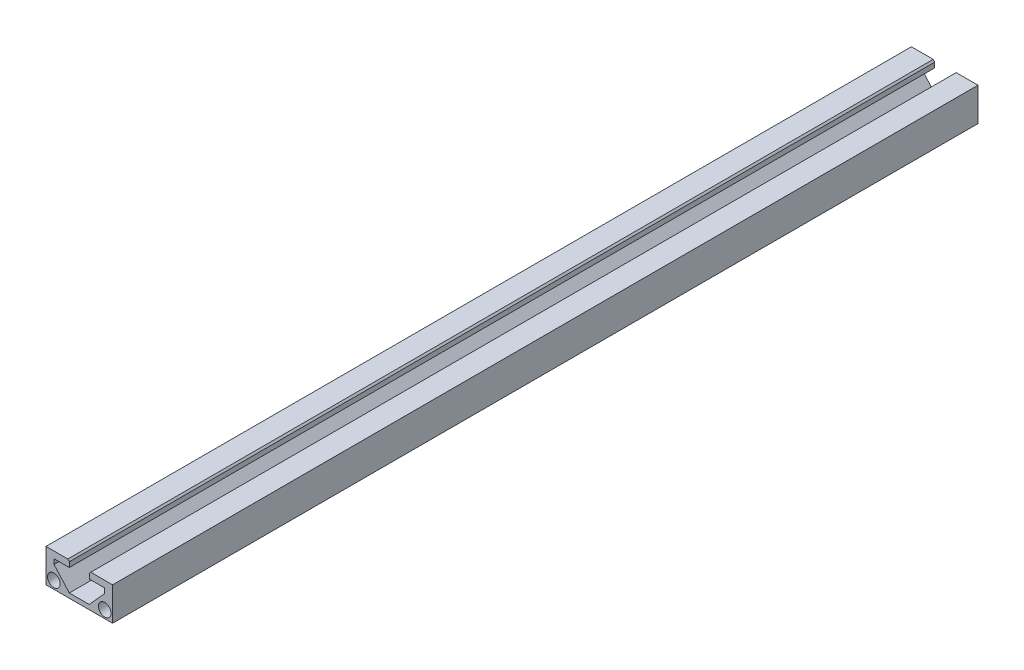
SolidWorks part; units mm, degrees
ref_plane "Front Plane" through (0, 0, 0) normal (0, 0, 1) x (1, 0, 0)
ref_plane "Top Plane" through (0, 0, 0) normal (0, 1, 0) x (1, 0, 0)
ref_plane "Right Plane" through (0, 0, 0) normal (1, 0, 0) x (0, 0, -1)
sketch "Sketch1" plane through (0, 0, 0) normal (0, 0, 1) x (1, 0, 0)
  line L0 (0, 0) -> (0, -1.383)
  line L1 (0, -1.383) -> (10, -1.383)
  line L2 (10, -1.383) -> (10, 8.617)
  line L3 (10, 8.617) -> (3.4482, 8.617)
  line L4 (3.4482, 8.617) -> (3, 8.117)
  line L5 (3, 8.117) -> (3, 6.617)
  line L6 (3, 6.617) -> (7.587, 6.617)
  line L7 (7.587, 6.617) -> (7.587, 5.117)
  line L8 (7.587, 5.117) -> (3, 0)
  line L9 (3, 0) -> (0, 0)
  dimension "D1" = 10
  dimension "D2" = 10
  dimension "D3" = 3
  dimension "D4" = 1.5
  dimension "D5" = 3
  dimension "D6" = 2
  dimension "D7" = 1.5
extrude "Boss-Extrude1" add sketch "Sketch1" along normal mid plane 260
mirror "Mirror1" about plane through (0, 0, 0) normal (1, 0, 0) of "Boss-Extrude1"
sketch "Sketch2" plane through (0, 0, 130) normal (0, 0, 1) x (1, 0, 0)
  line L0 (10, -1.383) -> (5.6551, 2.9619) construction
  line L1 (7.587, 5.117) -> (3, 0) construction
  circle A0 centre (7.6467, 0.9703) radius 1.9
  dimension "D1" = 3.8
extrude "Cut-Extrude1" cut sketch "Sketch2" against normal through all
mirror "Mirror2" about plane through (0, 0, 0) normal (1, 0, 0) of "Cut-Extrude1"
